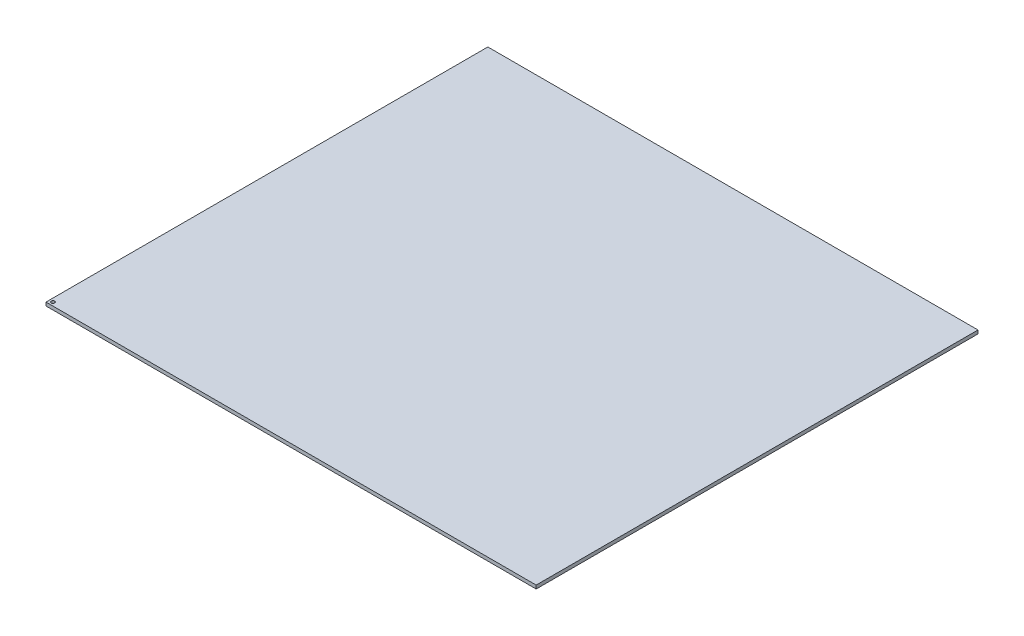
SolidWorks part; units mm, degrees
ref_plane "Front Plane" through (0, 0, 0) normal (0, 0, 1) x (1, 0, 0)
ref_plane "Top Plane" through (0, 0, 0) normal (0, 1, 0) x (1, 0, 0)
ref_plane "Right Plane" through (0, 0, 0) normal (1, 0, 0) x (0, 0, -1)
sketch "Sketch1" plane through (0, 0, 0) normal (0, 1, 0) x (1, 0, 0)
  line L1 (-450.85, -406.4) -> (450.85, -406.4)
  line L2 (-450.85, -406.4) -> (-450.85, 406.4)
  line L3 (-450.85, 406.4) -> (450.85, 406.4)
  line L4 (450.85, -406.4) -> (450.85, 406.4)
  line L5 (-450.85, -406.4) -> (450.85, 406.4) construction
  line L6 (-450.85, 406.4) -> (450.85, -406.4) construction
  point P0 (0, 0)
  dimension "D1" = 812.8
  dimension "D2" = 901.7
extrude "Boss-Extrude1" add sketch "Sketch1" along normal mid plane 6.35
sketch "Sketch2" plane through (0, 3.175, 0) normal (0, 1, 0) x (1, 0, 0)
  line L0 (-450.85, -406.4) -> (450.85, -406.4) construction
  line L1 (-450.85, 406.4) -> (-450.85, -406.4) construction
  circle A0 centre (-444.5, -400.05) radius 3.175
  dimension "D1" = 6.35
  dimension "D2" = 6.35
  dimension "D3" = 6.35
extrude "Cut-Extrude1" cut sketch "Sketch2" against normal through all
pattern_linear "LPattern1" [suppressed] count 64 spacing 12.7 count 71 spacing 12.7
